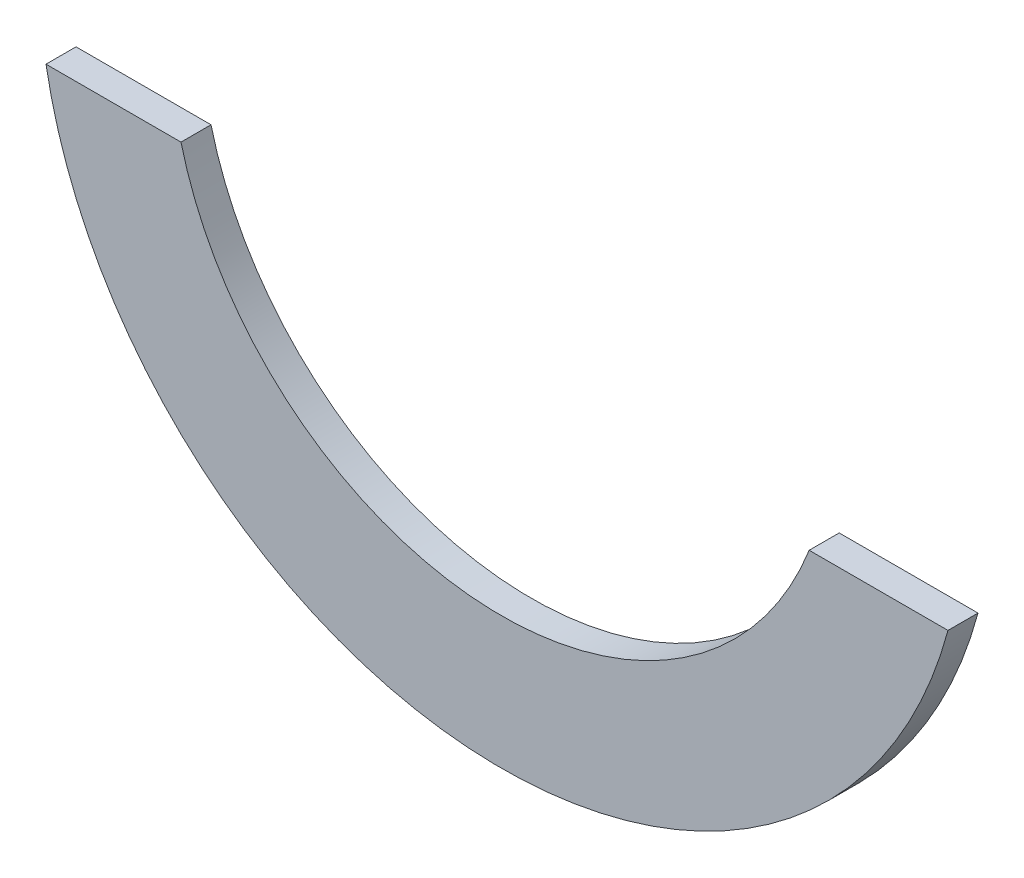
SolidWorks part; units mm, degrees
ref_plane "Front Plane" through (0, 0, 0) normal (0, 0, 1) x (1, 0, 0)
ref_plane "Top Plane" through (0, 0, 0) normal (0, 1, 0) x (1, 0, 0)
ref_plane "Right Plane" through (0, 0, 0) normal (1, 0, 0) x (0, 0, -1)
sketch "Sketch1" plane through (0, 0, 0) normal (0, 0, 1) x (1, 0, 0)
  line L0 (0, 0) -> (-75.8302, -13.3709) construction
  line L1 (0, 28.1055) -> (0, -101.384) construction
  line L2 (0, 0) -> (74.3763, -19.9291) construction
  line L3 (-58.91, -27.4702) -> (-60.7226, -28.3154) construction
  line L4 (61.08, -22.2313) -> (62.9594, -22.9153) construction
  line L5 (-75.8302, -13.3709) -> (-53.35, -13.3709)
  line L6 (74.3763, -19.9291) -> (51.2624, -19.9291)
  arc A0 (-58.91, -27.4702) -> (61.08, -22.2313) centre (0, 0) ccw construction
  arc A1 (-60.7226, -28.3154) -> (62.9594, -22.9153) centre (0, 0) ccw construction
  arc A2 (-75.8302, -13.3709) -> (74.3763, -19.9291) centre (0, 0) ccw
  arc A3 (-53.35, -13.3709) -> (51.2624, -19.9291) centre (0, 0) ccw
  dimension "D3" = 75
  dimension "D1" = 80
  dimension "D2" = 10
  dimension "D5" = 10
extrude "Boss-Extrude1" add sketch "Sketch1" along normal mid plane 5
